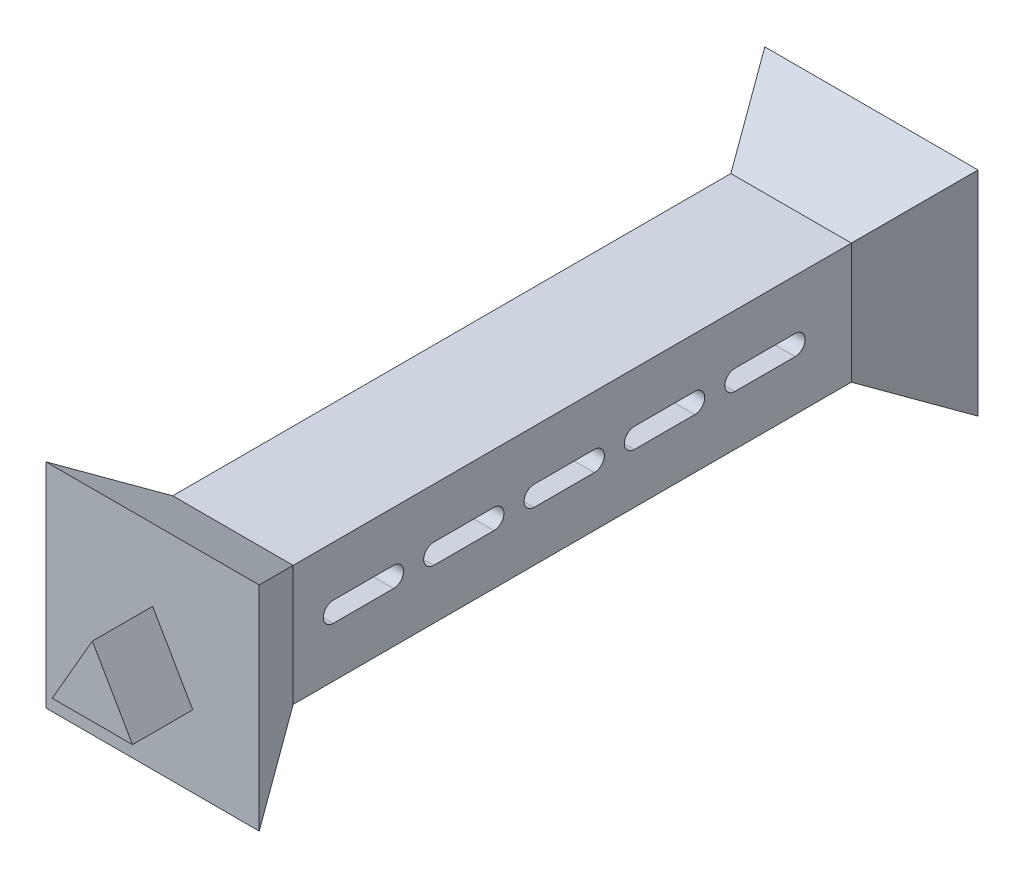
SolidWorks part; units mm, degrees
ref_plane "Front Plane" through (0, 0, 0) normal (0, 0, 1) x (1, 0, 0)
ref_plane "Top Plane" through (0, 0, 0) normal (0, 1, 0) x (1, 0, 0)
ref_plane "Right Plane" through (0, 0, 0) normal (1, 0, 0) x (0, 0, -1)
sketch "Sketch1" plane through (0, 0, 0) normal (0, 0, 1) x (1, 0, 0)
  line L1 (-1.5, 1.5) -> (1.5, 1.5)
  line L2 (-1.5, 1.5) -> (-1.5, -1.5)
  line L3 (-1.5, -1.5) -> (1.5, -1.5)
  line L4 (1.5, 1.5) -> (1.5, -1.5)
  line L5 (-1.5, 1.5) -> (1.5, -1.5) construction
  line L6 (-1.5, -1.5) -> (1.5, 1.5) construction
  point P0 (0, 0)
  dimension "D1" = 3
extrude "Boss-Extrude1" add sketch "Sketch1" along normal blind 13.9
ref_plane "Plane1" through (0, 0, 6.95) normal (0, 0, 1) x (1, 0, 0)
sketch "Sketch2" plane through (0, 0, 13.9) normal (0, 0, 1) x (1, 0, 0)
  line L4 (1.5, -1.5) -> (1.5, 1.5)
  line L5 (1.5, 1.5) -> (-1.5, 1.5)
  line L6 (-1.5, 1.5) -> (-1.5, -1.5)
  line L7 (-1.5, -1.5) -> (1.5, -1.5)
  line L8 (1.5, -1.5) -> (1.5, 1.5)
  line L9 (1.5, 1.5) -> (-1.5, 1.5)
  line L10 (-1.5, 1.5) -> (-1.5, -1.5)
  line L11 (-1.5, -1.5) -> (1.5, -1.5)
  dimension "D1" = 0
extrude "Boss-Extrude2" add sketch "Sketch2" along normal blind 2 draft 30 draft outward yes
mirror "Mirror1" about plane through (0, 0, 6.95) normal (0, 0, 1) of "Boss-Extrude2"
sketch "Sketch3" plane through (0, 0, 15.9) normal (0, 0, 1) x (1, 0, 0)
  line L0 (0, 0.866) -> (-1, -0.866)
  line L1 (-1, -0.866) -> (1, -0.866)
  line L2 (1, -0.866) -> (0, 0.866)
  line L3 (0, 0.866) -> (0, -0.866) construction
  line L4 (-0.5, 0) -> (1, -0.866) construction
  line L5 (-1, -0.866) -> (0.5, 0) construction
  line L6 (0, 2.6547) -> (0, -2.6547) construction
  line L7 (2.6547, 2.6547) -> (-2.6547, 2.6547) construction
  line L8 (-2.6547, -2.6547) -> (2.6547, -2.6547) construction
  line L9 (-2.6547, 0) -> (2.6547, 0) construction
  line L10 (-2.6547, 2.6547) -> (-2.6547, -2.6547) construction
  line L11 (2.6547, -2.6547) -> (2.6547, 2.6547) construction
  point P13 (0, 0)
  dimension "D1" = 2
extrude "Boss-Extrude3" add sketch "Sketch3" along normal blind 1.5
mirror "Mirror2" about plane through (0, 0, 6.95) normal (0, 0, 1) of "Boss-Extrude3"
sketch "Sketch7" plane through (1.5, 0, 0) normal (1, 0, 0) x (0, 0, -1)
  line L0 (-12.9, 0) -> (-11.4, 0) construction
  line L1 (-12.9, 0.25) -> (-11.4, 0.25)
  line L2 (-12.9, -0.25) -> (-11.4, -0.25)
  line L3 (-13.9, -1.5) -> (-13.9, 1.5) construction
  line L4 (-10.4, 0) -> (-8.9, 0) construction
  line L5 (-10.4, 0.25) -> (-8.9, 0.25)
  line L6 (-10.4, -0.25) -> (-8.9, -0.25)
  line L7 (-7.9, 0) -> (-6.4, 0) construction
  line L8 (-7.9, 0.25) -> (-6.4, 0.25)
  line L9 (-7.9, -0.25) -> (-6.4, -0.25)
  line L10 (-5.4, 0) -> (-3.9, 0) construction
  line L11 (-5.4, 0.25) -> (-3.9, 0.25)
  line L12 (-5.4, -0.25) -> (-3.9, -0.25)
  line L13 (-2.9, 0) -> (-1.4, 0) construction
  line L14 (-2.9, 0.25) -> (-1.4, 0.25)
  line L15 (-2.9, -0.25) -> (-1.4, -0.25)
  arc A0 (-12.9, 0.25) -> (-12.9, -0.25) centre (-12.9, 0) ccw
  arc A1 (-11.4, -0.25) -> (-11.4, 0.25) centre (-11.4, 0) ccw
  arc A2 (-10.4, 0.25) -> (-10.4, -0.25) centre (-10.4, 0) ccw
  arc A3 (-8.9, -0.25) -> (-8.9, 0.25) centre (-8.9, 0) ccw
  arc A4 (-7.9, 0.25) -> (-7.9, -0.25) centre (-7.9, 0) ccw
  arc A5 (-6.4, -0.25) -> (-6.4, 0.25) centre (-6.4, 0) ccw
  arc A6 (-5.4, 0.25) -> (-5.4, -0.25) centre (-5.4, 0) ccw
  arc A7 (-3.9, -0.25) -> (-3.9, 0.25) centre (-3.9, 0) ccw
  arc A8 (-2.9, 0.25) -> (-2.9, -0.25) centre (-2.9, 0) ccw
  arc A9 (-1.4, -0.25) -> (-1.4, 0.25) centre (-1.4, 0) ccw
  point P3 (-12.15, 0)
  point P11 (-13.9, 0)
  point P15 (-9.65, 0)
  point P22 (-7.15, 0)
  point P29 (-4.65, 0)
  point P36 (-2.15, 0)
  dimension "D1" = 1.5
  dimension "D3" = 1
  dimension "D5" = 1
  dimension "D2" = 0.5
  dimension "D4" = 5
extrude "Cut-Extrude1" cut sketch "Sketch7" against normal up to next
